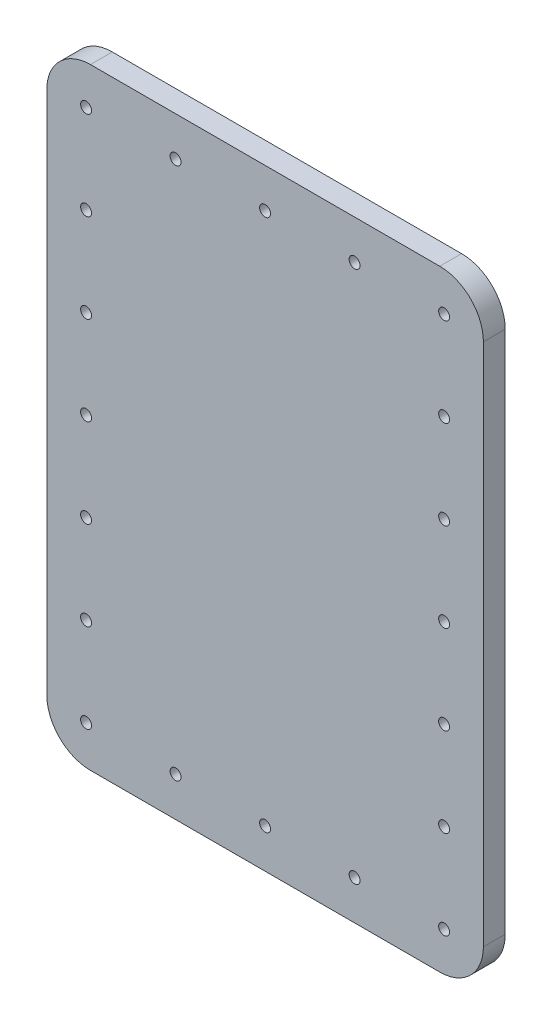
SolidWorks part; units mm, degrees
ref_plane "Front Plane" through (0, 0, 0) normal (0, 0, 1) x (1, 0, 0)
ref_plane "Top Plane" through (0, 0, 0) normal (0, 1, 0) x (1, 0, 0)
ref_plane "Right Plane" through (0, 0, 0) normal (1, 0, 0) x (0, 0, -1)
sketch "Sketch1" plane through (0, 0, 0) normal (0, 0, 1) x (1, 0, 0)
  line L0 (0, 0) -> (-41, 0) construction
  line L1 (-50, -70) -> (50, -70)
  line L2 (-50, -70) -> (-50, 70)
  line L3 (-50, 70) -> (50, 70)
  line L4 (50, -70) -> (50, 70)
  line L5 (-50, -70) -> (50, 70) construction
  line L6 (-50, 70) -> (50, -70) construction
  line L7 (-41, -61) -> (41, -61) construction
  line L8 (-41, -61) -> (-41, 61) construction
  line L9 (-41, 61) -> (41, 61) construction
  line L10 (41, -61) -> (41, 61) construction
  line L11 (-41, -61) -> (41, 61) construction
  line L12 (-41, 61) -> (41, -61) construction
  line L13 (0, 0) -> (0, 44.6853) construction
  circle A0 centre (0, 61) radius 1.25
  circle A1 centre (-41, 61) radius 1.25
  circle A2 centre (-20.5, 61) radius 1.25
  circle A3 centre (20.5, 61) radius 1.25
  circle A4 centre (41, 61) radius 1.25
  circle A5 centre (-41, 0) radius 1.25
  circle A6 centre (-41, 40.6667) radius 1.25
  circle A7 centre (-41, 20.3333) radius 1.25
  circle A8 centre (41, 40.6667) radius 1.25
  circle A9 centre (41, 20.3333) radius 1.25
  circle A10 centre (41, 0) radius 1.25
  circle A11 centre (-20.5, -61) radius 1.25
  circle A12 centre (0, -61) radius 1.25
  circle A13 centre (20.5, -61) radius 1.25
  circle A14 centre (41, -61) radius 1.25
  circle A15 centre (41, -40.6667) radius 1.25
  circle A16 centre (41, -20.3333) radius 1.25
  circle A17 centre (-41, -20.3333) radius 1.25
  circle A18 centre (-41, -40.6667) radius 1.25
  circle A19 centre (-41, -61) radius 1.25
  point P0 (0, 0)
  point P6 (0, 0)
  dimension "D5" = 20.5
  dimension "D7" = 2.5
  dimension "D1" = 100
  dimension "D2" = 140
  dimension "D3" = 9
  dimension "D4" = 9
  dimension "D6" = 20.5
  dimension "D8" = 20.3333
  dimension "D9" = 20.3333
extrude "Boss-Extrude1" add sketch "Sketch1" along normal blind 5
fillet "Fillet1" radius 10 4 edges at (-50, -70, 2.5) (50, -70, 2.5) (-50, 70, 2.5) (50, 70, 2.5)
